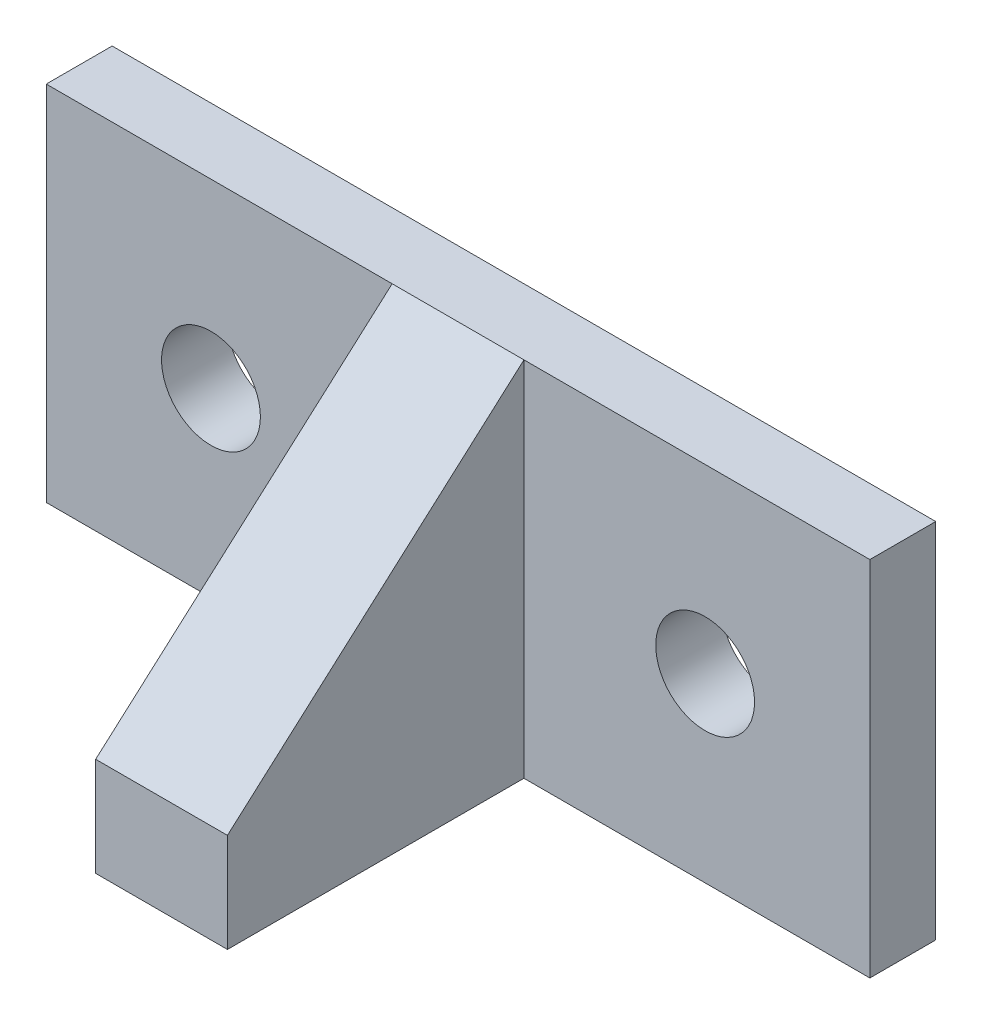
SolidWorks part; units mm, degrees
ref_plane "Front Plane" through (0, 0, 0) normal (0, 0, 1) x (1, 0, 0)
ref_plane "Top Plane" through (0, 0, 0) normal (0, 1, 0) x (1, 0, 0)
ref_plane "Right Plane" through (0, 0, 0) normal (1, 0, 0) x (0, 0, -1)
sketch "Sketch1" plane through (0, 0, 0) normal (0, 0, 1) x (1, 0, 0)
  line L0 (0, 0) -> (0, 61.2583) construction
  line L1 (62.5, -27.5) -> (-62.5, -27.5)
  line L2 (62.5, -27.5) -> (62.5, 27.5)
  line L3 (62.5, 27.5) -> (-62.5, 27.5)
  line L4 (-62.5, -27.5) -> (-62.5, 27.5)
  line L5 (62.5, -27.5) -> (-62.5, 27.5) construction
  line L6 (62.5, 27.5) -> (-62.5, -27.5) construction
  circle A0 centre (-37.5, 0) radius 7.5
  circle A1 centre (37.5, 0) radius 7.5
  point P0 (0, 0)
  point P12 (0, 0)
  point P13 (-37.5, 7.6573)
  dimension "D3" = 15
  dimension "D1" = 125
  dimension "D2" = 55
  dimension "D4" = 75
extrude "Boss-Extrude1" add sketch "Sketch1" along normal blind 10
sketch "Sketch2" plane through (0, 0, 0) normal (1, 0, 0) x (0, 0, -1)
  line L0 (0, -27.5) -> (-55, -27.5)
  line L1 (-55, -27.5) -> (-55, -12.5)
  line L2 (-55, -12.5) -> (-10, 27.5)
  line L3 (-10, -27.5) -> (-10, 27.5) construction
  line L4 (-10, 27.5) -> (0, 27.5) construction
  line L5 (-10, 27.5) -> (0, 27.5)
  line L6 (0, 27.5) -> (0, -27.5)
  dimension "D1" = 55
  dimension "D2" = 15
extrude "Boss-Extrude2" add sketch "Sketch2" along normal mid plane 20
